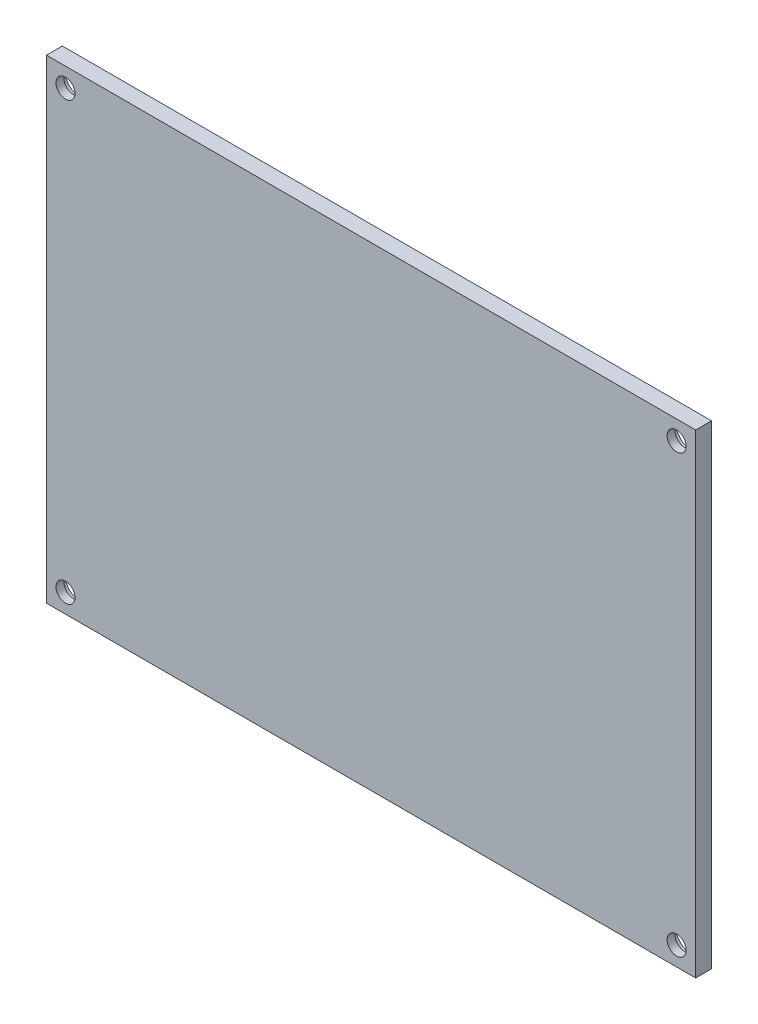
SolidWorks part; units mm, degrees
ref_plane "Front Plane" through (0, 0, 0) normal (0, 0, 1) x (1, 0, 0)
ref_plane "Top Plane" through (0, 0, 0) normal (0, 1, 0) x (1, 0, 0)
ref_plane "Right Plane" through (0, 0, 0) normal (1, 0, 0) x (0, 0, -1)
sketch "Sketch1" plane through (0, 0, 0) normal (0, 0, 1) x (1, 0, 0)
  line L16 (136.4912, -26.7639) -> (136.4912, 33.0361)
  line L17 (54.6912, -26.7639) -> (136.4912, -26.7639)
  line L18 (54.6912, 33.0361) -> (54.6912, -26.7639)
  line L19 (136.4912, 33.0361) -> (54.6912, 33.0361)
  line L20 (136.4912, -26.7639) -> (136.4912, 33.0361)
  line L21 (54.6912, -26.7639) -> (136.4912, -26.7639)
  line L22 (54.6912, 33.0361) -> (54.6912, -26.7639)
  line L23 (136.4912, 33.0361) -> (54.6912, 33.0361)
  dimension "D1" = 0.1
extrude "Boss-Extrude1" add sketch "Sketch1" along normal blind 2
hole_wizard "CBORE for M2 Pan Head Machine Screw1" positions "Sketch4" profile "Sketch3" counterbore size "M2" standard "ANSI Metric"
sketch "Sketch4" plane through (0, 0, 0) normal (0, 0, -1) x (-1, 0, 0)
  point P14 (-57.0912, 30.6361)
  point P17 (-134.0912, 30.6361)
  point P23 (-57.0912, -24.3639)
  point P26 (-134.0912, -24.3639)
sketch "Sketch3" plane through (57.0912, 30.6361, 0) normal (1, 0, 0) x (0, 1, 0)
  line L0 (0, 0) -> (0, 6.721)
  line L1 (0, 6.721) -> (1.2, 6)
  line L2 (1.2, 6) -> (1.2, 1)
  line L3 (1.2, 1) -> (2.125, 1)
  line L4 (2.125, 1) -> (2.125, 0)
  line L5 (2.125, 0) -> (0, 0)
  line L10 (0, 6.721) -> (-1.2, 6) construction
  line L11 (0, -6.35) -> (0, 107.95) construction
  dimension "Hole Dia." = 2.4
  dimension "Hole Depth" = 6
  dimension "C'Bore Dia." = 4.25
  dimension "C'Bore Depth" = 1
  dimension "Drill Angle" = 118
